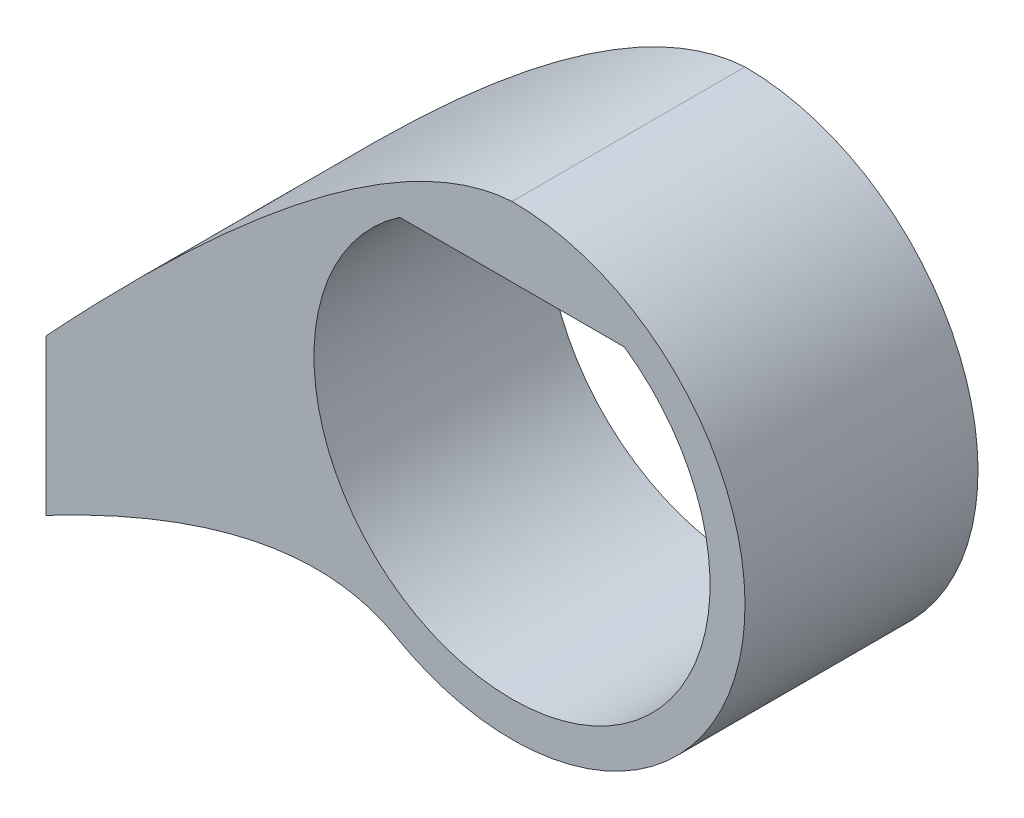
SolidWorks part; units mm, degrees
ref_plane "Vorne" through (0, 0, 0) normal (0, 0, 1) x (1, 0, 0)
ref_plane "Oben" through (0, 0, 0) normal (0, 1, 0) x (1, 0, 0)
ref_plane "Seite" through (0, 0, 0) normal (1, 0, 0) x (0, 0, -1)
sketch "Skizze1" plane through (0, 0, 0) normal (0, 0, 1) x (1, 0, 0)
  line L0 (-12, -7) -> (-12, -3)
  line L1 (2.8931, 4.2) -> (-2.8931, 4.2)
  arc A0 (-2.8931, 4.2) -> (2.8931, 4.2) centre (0, 0) ccw
  arc A1 (-3, -5.1962) -> (0, 6) centre (0, 0) ccw
  spline S0 degree 2 poles (-12, -3) (-3.8464, 5.7713) (0, 6) knots 0 0 0 0.663529 0.663529 0.663529
  spline S1 degree 2 poles (-12, -7) (-5.6542, -3.6637) (-3, -5.1962) knots 0 0 0 0.361848 0.361848 0.361848
  dimension "D3" = 10.2
  dimension "D4" = 6
  dimension "D5" = 4
  dimension "D1" = 12
  dimension "D2" = 7
  dimension "D6" = 3
  dimension "D7" = 4.2
extrude "Aufsatz-Linear austragen1" add sketch "Skizze1" along normal blind 6
